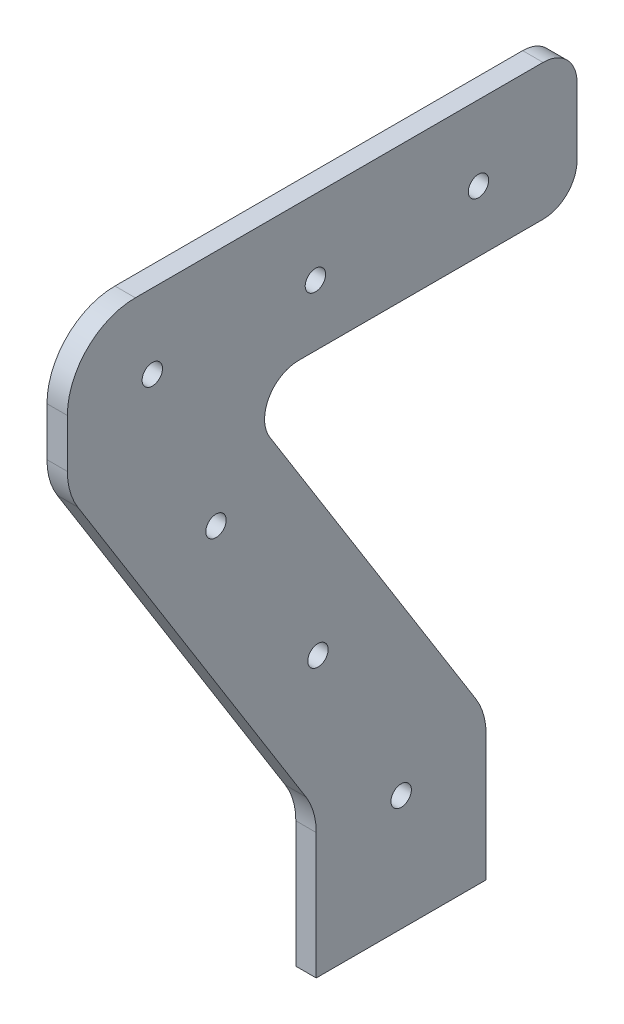
SolidWorks part; units mm, degrees
ref_plane "Alzado" through (0, 0, 0) normal (0, 0, 1) x (1, 0, 0)
ref_plane "Planta" through (0, 0, 0) normal (0, 1, 0) x (1, 0, 0)
ref_plane "Vista lateral" through (0, 0, 0) normal (1, 0, 0) x (0, 0, -1)
sketch "Croquis1" plane through (0, 0, 0) normal (1, 0, 0) x (0, 0, -1)
  line L1 (0, 0) -> (75, 0)
  line L2 (0, 0) -> (0, -100)
  line L3 (0, -100) -> (75, -100)
  line L4 (75, 0) -> (75, -100)
  dimension "D1" = 100
  dimension "D2" = 75
extrude "Saliente-Extruir1" add sketch "Croquis1" along normal blind 3
sketch "Croquis2" plane through (3, 0, 0) normal (1, 0, 0) x (0, 0, -1)
  line L1 (25, -20) -> (75, -20)
  line L4 (75, -20) -> (75, -100)
  line L6 (25, -20) -> (61.622, -78.5952)
  line L7 (0, 0) -> (0, -100) construction
  line L8 (0, -20) -> (0, 0)
  line L9 (0, 0) -> (75, 0)
  line L10 (75, 0) -> (75, -20)
  line L12 (61.622, -100) -> (61.622, -78.5952)
  line L13 (61.622, -78.5952) -> (36.622, -78.5952) construction
  line L14 (36.622, -78.5952) -> (36.622, -100)
  line L15 (0, -100) -> (75, -100) construction
  line L16 (0, -20) -> (36.622, -78.5952)
  line L17 (36.622, -100) -> (61.622, -100)
  dimension "D1" = 21.2
  dimension "D2" = 50
  dimension "D3" = 21.4048
  dimension "D4" = 20
  dimension "D5" = 25
extrude "Cortar-Extruir1" cut sketch "Croquis2" against normal blind 3
fillet "Redondeo1" radius 10 4 edges at (1.5, 0, 0) (1.5, -20, 0) (1.5, -78.5952, -61.622) (1.5, -78.5952, -36.622)
fillet "Redondeo3" radius 5 3 edges at (1.5, 0, -75) (1.5, -20, -75) (1.5, -20, -25)
sketch "Croquis3" plane through (3, 0, 0) normal (1, 0, 0) x (0, 0, -1)
  line L0 (0, -10) -> (0, -17.132) construction
  line L1 (70, 0) -> (10, 0) construction
  line L4 (70, -20) -> (34.0212, -20) construction
  line L5 (29.7812, -27.65) -> (60.102, -76.1631) construction
  line L6 (34.375, -35) -> (21.875, -35) construction
  line L7 (49.375, -59) -> (36.875, -59) construction
  line L8 (61.622, -83) -> (49.122, -83) construction
  line L9 (61.622, -100) -> (61.622, -81.4631) construction
  line L10 (36.622, -81.4631) -> (36.622, -100) construction
  line L11 (1.52, -22.432) -> (35.102, -76.1631) construction
  circle A0 centre (12.5, -11) radius 1.5
  circle A2 centre (12.5, -83) radius 1.5
  circle A5 centre (36.5, -11) radius 1.5
  circle A6 centre (60.5, -11) radius 1.5
  circle A7 centre (21.875, -35) radius 1.5
  circle A8 centre (36.875, -59) radius 1.5
  circle A9 centre (49.122, -83) radius 1.5
  dimension "D1" = 3
  dimension "D3" = 10.6
  dimension "D4" = 3
  dimension "D5" = 25.7661
  dimension "D6" = 11
  dimension "D7" = 12.5
  dimension "D8" = 28.3019
  dimension "D9" = 3
  dimension "D10" = 26.9442
  dimension "D11" = 3
  dimension "D14" = 3
  dimension "D15" = 24
  dimension "D16" = 24
  dimension "D17" = 9
  dimension "D18" = 9
  dimension "D19" = 3
  dimension "D20" = 12.5
  dimension "D21" = 10.6
extrude "Cortar-Extruir2" cut sketch "Croquis3" against normal blind 3
